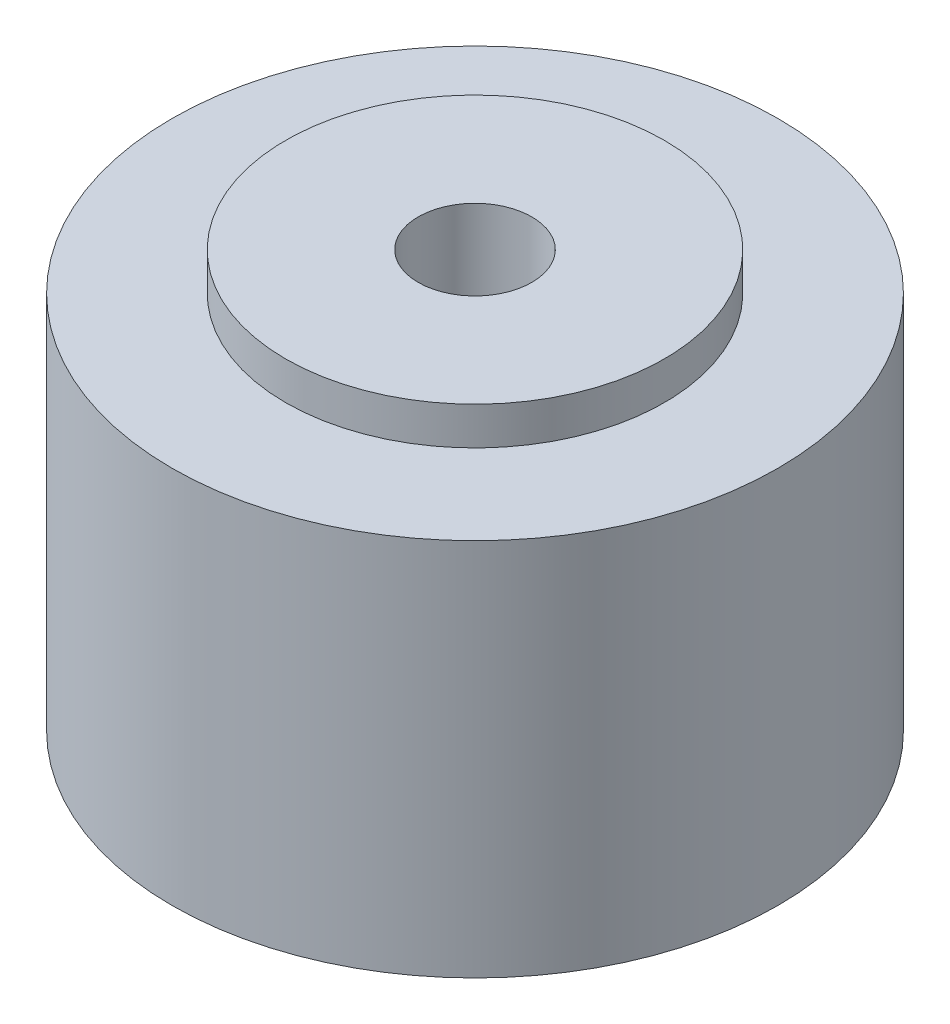
SolidWorks part; units mm, degrees
ref_plane "前视基准面" through (0, 0, 0) normal (0, 0, 1) x (1, 0, 0)
ref_plane "上视基准面" through (0, 0, 0) normal (0, 1, 0) x (1, 0, 0)
ref_plane "右视基准面" through (0, 0, 0) normal (1, 0, 0) x (0, 0, -1)
other "Configuration Table"
sketch "草图1" plane through (0, 0, 0) normal (0, 1, 0) x (1, 0, 0)
  circle A0 centre (0, 0) radius 2.5
  circle A1 centre (0, 0) radius 0.75
  dimension "D1" = 5
  dimension "D2" = 1.5
extrude "凸台-拉伸1" add sketch "草图1" along normal mid plane 6
sketch "草图2" plane through (0, 0, 0) normal (0, 1, 0) x (1, 0, 0)
  circle A0 centre (0, 0) radius 4
  circle A1 centre (0, 0) radius 2.5 construction
  circle A2 centre (0, 0) radius 2.5
  dimension "D1" = 8
extrude "凸台-拉伸2" add sketch "草图2" along normal mid plane 5
